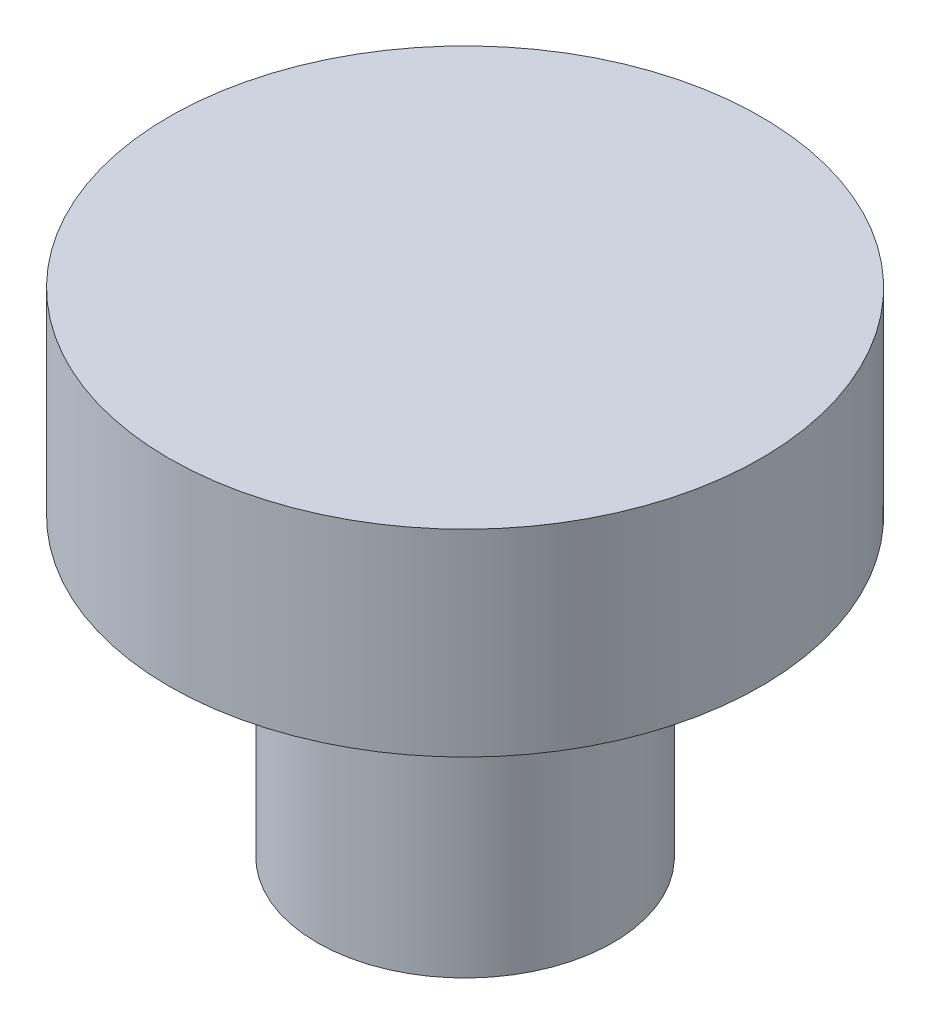
SolidWorks part; units mm, degrees
ref_plane "Front Plane" through (0, 0, 0) normal (0, 0, 1) x (1, 0, 0)
ref_plane "Top Plane" through (0, 0, 0) normal (0, 1, 0) x (1, 0, 0)
ref_plane "Right Plane" through (0, 0, 0) normal (1, 0, 0) x (0, 0, -1)
sketch "Sketch1" plane through (0, 0, 0) normal (0, 1, 0) x (1, 0, 0)
  circle A0 centre (0, 0) radius 1.5
  dimension "D1" = 3
extrude "Boss-Extrude1" add sketch "Sketch1" along normal blind 3
sketch "Sketch2" plane through (0, 3, 0) normal (0, 1, 0) x (1, 0, 0)
  circle A0 centre (0, 0) radius 3
  dimension "D1" = 6
extrude "Boss-Extrude2" add sketch "Sketch2" along normal blind 2
